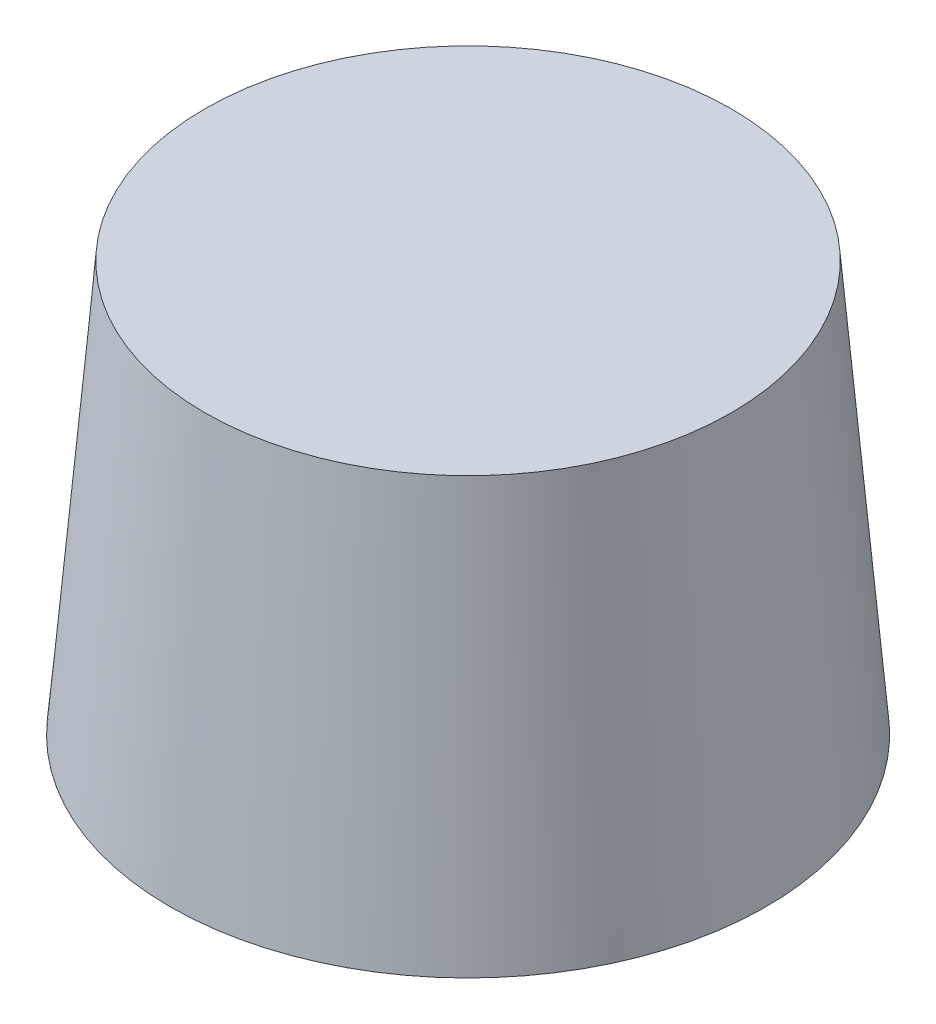
SolidWorks part; units mm, degrees
ref_plane "Front Plane" through (0, 0, 0) normal (0, 0, 1) x (1, 0, 0)
ref_plane "Top Plane" through (0, 0, 0) normal (0, 1, 0) x (1, 0, 0)
ref_plane "Right Plane" through (0, 0, 0) normal (1, 0, 0) x (0, 0, -1)
ref_axis "Axis1" through (0, 37.6932, 0) along (0, -1, 0)
sketch "Sketch2" plane through (0, 0, 0) normal (0, 0, 1) x (1, 0, 0)
  line L0 (0, 53) -> (34, 53)
  line L1 (34, 53) -> (38.5, 0)
  line L2 (38.5, 0) -> (0, 0)
  line L3 (0, 0) -> (0, 53)
  point P0 (0, 0)
  point P5 (1.4057, 63.2578)
  dimension "D1" = 34
  dimension "D2" = 38.5
  dimension "D3" = 53
revolve "Revolve1" add sketch "Sketch2" angle 360 about axis through (0, 37.6932, 0) along (0, -1, 0)
equation "\"D2@Sketch2\"=77/2"
